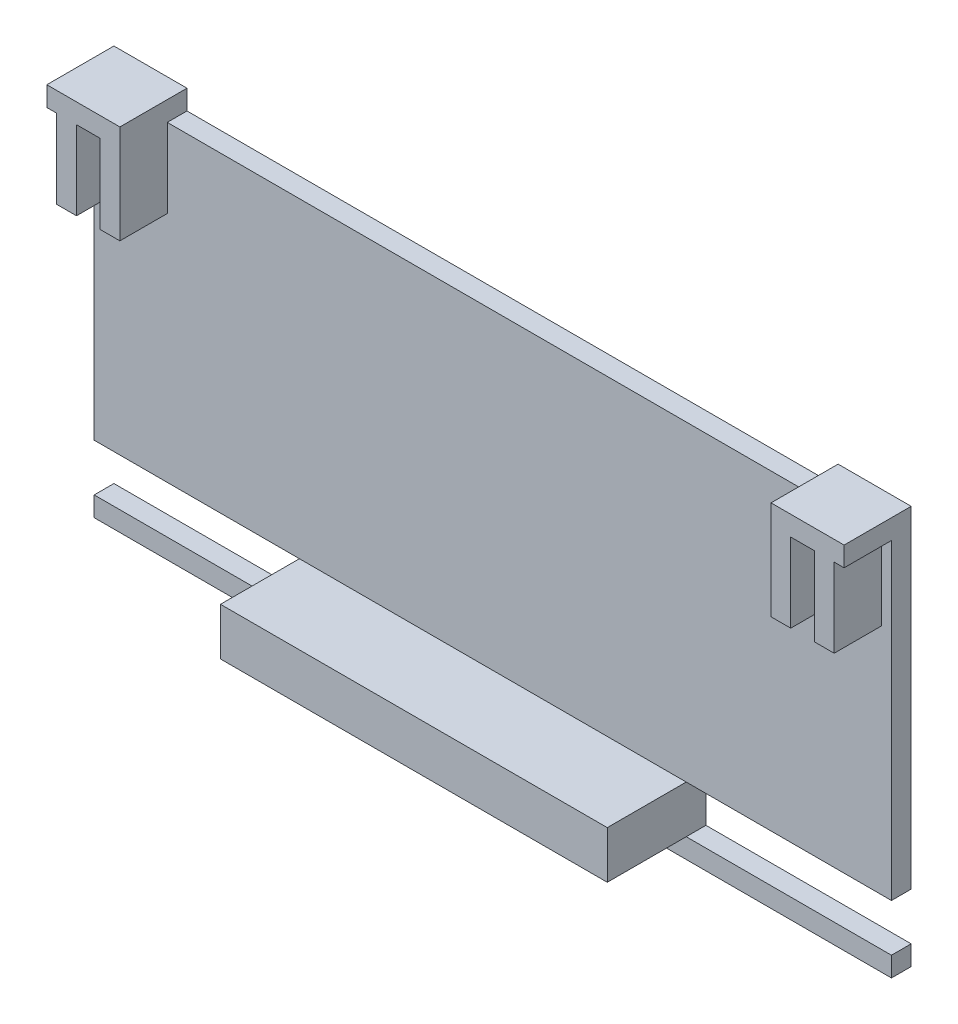
SolidWorks part; units mm, degrees
ref_plane "Front" through (0, 0, 0) normal (0, 0, 1) x (1, 0, 0)
ref_plane "Top" through (0, 0, 0) normal (0, 1, 0) x (1, 0, 0)
ref_plane "Right" through (0, 0, 0) normal (1, 0, 0) x (0, 0, -1)
sketch "Sketch1" plane through (0, 0, 0) normal (0, 0, 1) x (1, 0, 0)
  line L0 (-1.25, 0) -> (-1.25, 24)
  line L1 (-1.25, 0) -> (49.25, 0)
  line L2 (0, 0) -> (0, 22.75) construction
  line L3 (-1.25, 22.75) -> (49.25, 22.75) construction
  line L4 (48, 0) -> (48, 22.75) construction
  line L5 (-1.25, 24) -> (49.25, 24)
  line L6 (49.25, 0) -> (49.25, 24)
  line L7 (-1.25, 0) -> (-1.25, 22.75) construction
  line L8 (49.25, 0) -> (49.25, 22.75) construction
  dimension "D1" = 22.75
  dimension "D2" = 48
  dimension "D3" = 1.25
  dimension "D4" = 1.25
  dimension "D5" = 1.25
extrude "Boss-Extrude1" add sketch "Sketch1" along normal blind 1.25
sketch "Sketch2" plane through (0, 24, 0) normal (0, 1, 0) x (1, 0, 0)
  line L0 (49.25, -1.25) -> (-1.25, -1.25) construction
  line L1 (47.3715, -1.25) -> (48.6215, -1.25)
  line L2 (47.3715, -1.25) -> (47.3715, -4.25)
  line L3 (47.3715, -4.25) -> (48.6215, -4.25)
  line L4 (48.6215, -1.25) -> (48.6215, -4.25)
  line L6 (45.8715, -1.25) -> (44.6215, -1.25)
  line L7 (45.8715, -1.25) -> (45.8715, -4.25)
  line L8 (45.8715, -4.25) -> (44.6215, -4.25)
  line L9 (44.6215, -1.25) -> (44.6215, -4.25)
  line L10 (24, 0) -> (24, 4.2372) construction
  line L11 (49.25, 0) -> (-1.25, 0) construction
  line L12 (3.3785, -1.25) -> (3.3785, -4.25)
  line L13 (2.1285, -4.25) -> (3.3785, -4.25)
  line L14 (2.1285, -1.25) -> (2.1285, -4.25)
  line L15 (2.1285, -1.25) -> (3.3785, -1.25)
  line L16 (-0.6215, -1.25) -> (-0.6215, -4.25)
  line L17 (0.6285, -4.25) -> (-0.6215, -4.25)
  line L18 (0.6285, -1.25) -> (0.6285, -4.25)
  line L19 (0.6285, -1.25) -> (-0.6215, -1.25)
  dimension "D1" = 1.5
  dimension "D2" = 3
  dimension "D3" = 1.25
extrude "Boss-Extrude2" add sketch "Sketch2" against normal blind 5
sketch "Sketch3" plane through (0, 0, 0) normal (0, 0, -1) x (-1, 0, 0)
  line L0 (-49.25, 0) -> (-49.25, 24) construction
  line L1 (-49.25, 1.25) -> (-36.25, 1.25)
  line L2 (-49.25, 1.25) -> (-49.25, 4.25)
  line L3 (-49.25, 4.25) -> (-36.25, 4.25)
  line L4 (-36.25, 1.25) -> (-36.25, 4.25)
  line L5 (1.25, 0) -> (-49.25, 0) construction
  line L6 (-24, 0) -> (-24, 7.297) construction
  line L7 (-11.75, 1.25) -> (-11.75, 4.25)
  line L8 (1.25, 1.25) -> (-11.75, 1.25)
  line L9 (1.25, 4.25) -> (-11.75, 4.25)
  line L10 (1.25, 1.25) -> (1.25, 4.25)
  dimension "D1" = 3
  dimension "D2" = 1.25
  dimension "D3" = 13
extrude "Cut-Extrude1" cut sketch "Sketch3" against normal up to surface (1.25 mm away) up to face at (25.1375, 19.35, 1.25)
sketch "Sketch5" plane through (0, 24, 0) normal (0, 1, 0) x (1, 0, 0)
  line L1 (3.3785, 0) -> (-1.25, 0)
  line L2 (44.6215, -4.25) -> (49.25, -4.25)
  line L3 (44.6215, -4.25) -> (44.6215, 0)
  line L4 (44.6215, 0) -> (49.25, 0)
  line L5 (24, -1.25) -> (24, 0) construction
  line L6 (44.6215, -1.25) -> (3.3785, -1.25) construction
  line L7 (49.25, 0) -> (-1.25, 0) construction
  line L8 (49.25, -4.25) -> (49.25, 0)
  line L9 (3.3785, -4.25) -> (3.3785, 0)
  line L10 (3.3785, -4.25) -> (-1.25, -4.25)
  line L11 (-1.25, -4.25) -> (-1.25, 0)
extrude "Boss-Extrude3" add sketch "Sketch5" along normal blind 1.25
sketch "Sketch9" plane through (0, 0, 1.25) normal (0, 0, 1) x (1, 0, 0)
  line L0 (11.75, 1.25) -> (36.25, 1.25)
  line L1 (11.75, 1.25) -> (11.75, 4.25)
  line L2 (36.25, 1.25) -> (36.25, 4.25)
  line L3 (11.75, 4.25) -> (36.25, 4.25)
  line L4 (49.25, 1.25) -> (36.25, 1.25) construction
extrude "Boss-Extrude5" add sketch "Sketch9" along normal blind 5
